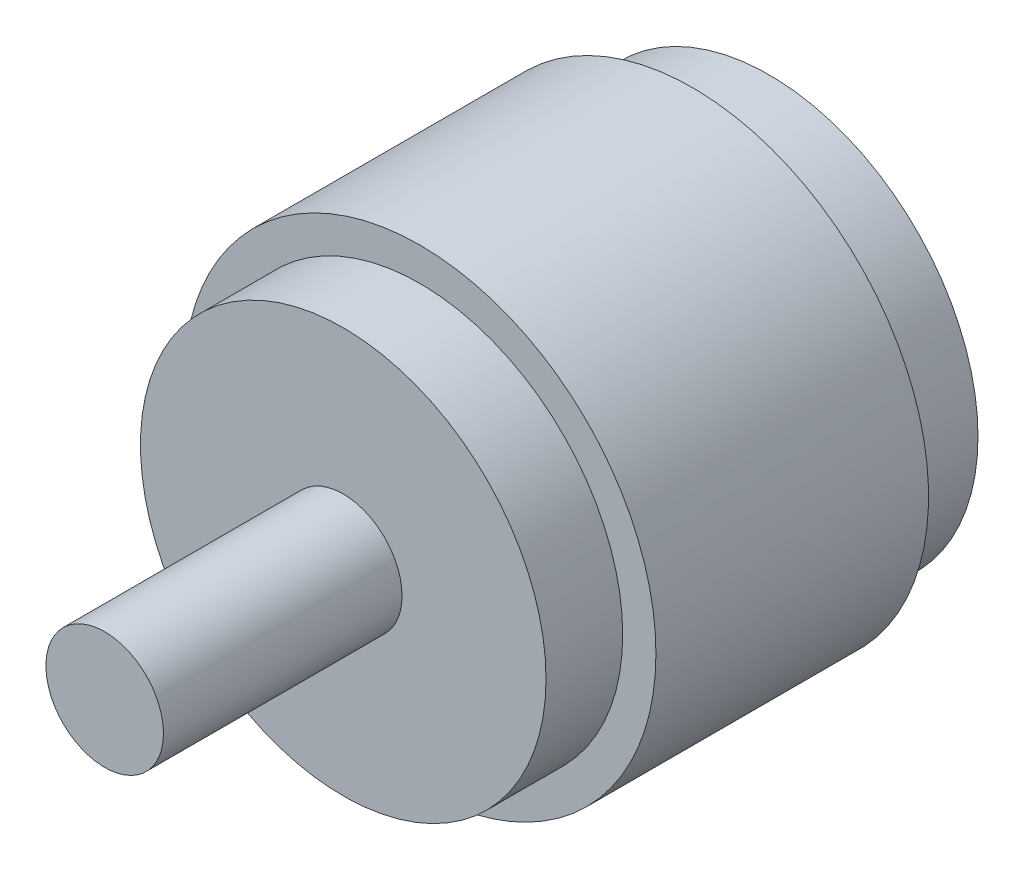
SolidWorks part; units mm, degrees
material "201.0-T43 Insulated Mold Casting (SS)"
ref_plane "Front Plane" through (0, 0, 0) normal (0, 0, 1) x (1, 0, 0)
ref_plane "Top Plane" through (0, 0, 0) normal (0, 1, 0) x (1, 0, 0)
ref_plane "Right Plane" through (0, 0, 0) normal (1, 0, 0) x (0, 0, -1)
sketch "Sketch1" plane through (0, 0, 0) normal (0, 0, 1) x (1, 0, 0)
  circle A0 centre (0, 0) radius 13.85
  dimension "D1" = 27.7
extrude "Boss-Extrude1" add sketch "Sketch1" along normal blind 25
sketch "Sketch2" plane through (0, 0, 25) normal (0, 0, 1) x (1, 0, 0)
  circle A0 centre (0, 0) radius 11.9
  dimension "D1" = 23.8
extrude "Cut-Extrude3" cut sketch "Sketch2" against normal blind 4.5 flip side to cut contours A0
sketch "Sketch6" plane through (0, 0, 0) normal (0, 0, -1) x (-1, 0, 0)
  circle A0 centre (0, 0) radius 12.25
  dimension "D1" = 24.5
extrude "Cut-Extrude5" cut sketch "Sketch6" against normal blind 4.5 flip side to cut contours A0
sketch "Sketch7" plane through (0, 0, 25) normal (0, 0, 1) x (1, 0, 0)
  circle A0 centre (0, 0) radius 3.45
  dimension "D1" = 6.9
extrude "Boss-Extrude2" add sketch "Sketch7" along normal blind 14 contours A0
sketch "Sketch9" plane through (0, 0, 0) normal (0, 0, -1) x (-1, 0, 0)
  line L2 (-6.125, 0) -> (-6.125, 10.6088) construction
  line L4 (6.125, 10.6088) -> (6.125, 0) construction
  line L5 (6.125, 0) -> (6.125, -10.6088) construction
  line L7 (-6.125, -10.6088) -> (-6.125, 0) construction
  circle A0 centre (0, 0) radius 12.25 construction
  circle A1 centre (0, 0) radius 12.25 construction
hole_wizard "CSK for M3 Oval Head Machine Screw2" positions "Sketch14" profile "Sketch15" countersink size "M3" standard "ANSI Metric"
sketch "Sketch14" plane through (0, 0, 0) normal (0, 0, -1) x (-1, 0, 0)
  line L0 (-6.125, 0) -> (-6.125, 10.6088) construction
  line L1 (6.125, 10.6088) -> (6.125, 0) construction
  line L2 (6.125, 0) -> (6.125, -10.6088) construction
  line L3 (-6.125, -10.6088) -> (-6.125, 0) construction
  point P0 (-6.125, 5.3044)
  point P4 (6.125, 5.3044)
  point P8 (6.125, -5.3044)
  point P12 (-6.125, -5.3044)
sketch "Sketch15" plane through (6.125, 5.3044, 0) normal (1, 0, 0) x (0, 1, 0)
  line L0 (0, 0) -> (0, 6.0215)
  line L1 (0, 6.0215) -> (1.7, 5)
  line L2 (1.7, 5) -> (1.7, 0.3)
  line L3 (1.7, 0.3) -> (2, 0)
  line L5 (2, 0) -> (0, 0)
  line L6 (-1.7, 0.3) -> (-2, 0) construction
  line L10 (0, 6.0215) -> (-1.7, 5) construction
  line L11 (0, -6.35) -> (0, 107.95) construction
  dimension "Hole Dia." = 3.4
  dimension "Hole Depth" = 5
  dimension "Near C'Sink Dia." = 4
  dimension "Near C'Sink Angle" = 90
  dimension "Drill Angle" = 118
